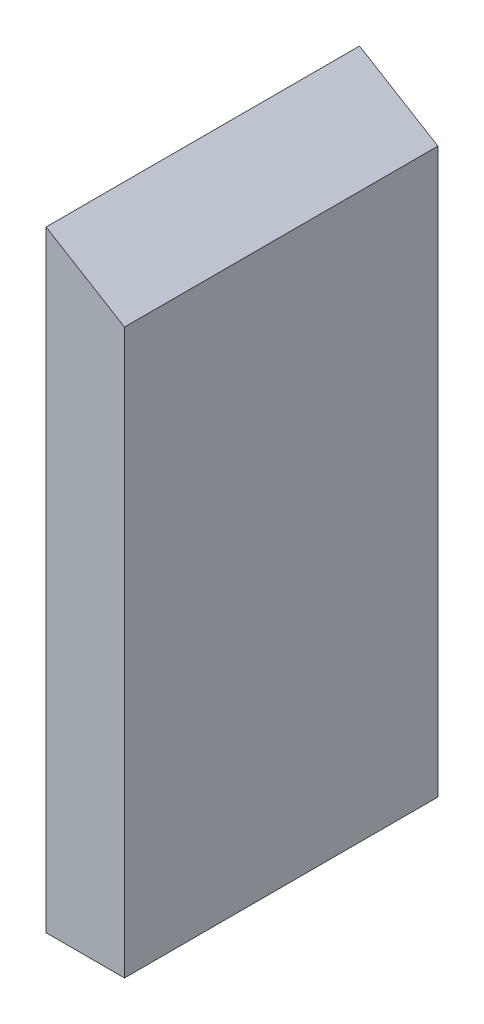
SolidWorks part; units mm, degrees
ref_plane "Front Plane" through (0, 0, 0) normal (0, 0, 1) x (1, 0, 0)
ref_plane "Top Plane" through (0, 0, 0) normal (0, 1, 0) x (1, 0, 0)
ref_plane "Right Plane" through (0, 0, 0) normal (1, 0, 0) x (0, 0, -1)
sketch "Sketch1" plane through (0, 0, 0) normal (0, 0, 1) x (1, 0, 0)
  line L0 (0, 0) -> (0, 78)
  line L1 (0, 0) -> (10, 0)
  line L2 (10, 0) -> (10, 71.9366)
  line L3 (0, 78) -> (10, 71.9366)
  dimension "D1" = 78
  dimension "D2" = 10
  dimension "D3" = 58.77
  dimension "D4" = 11.6946
extrude "Boss-Extrude1" add sketch "Sketch1" along normal blind 40 contours L2 L3 L0 L1
